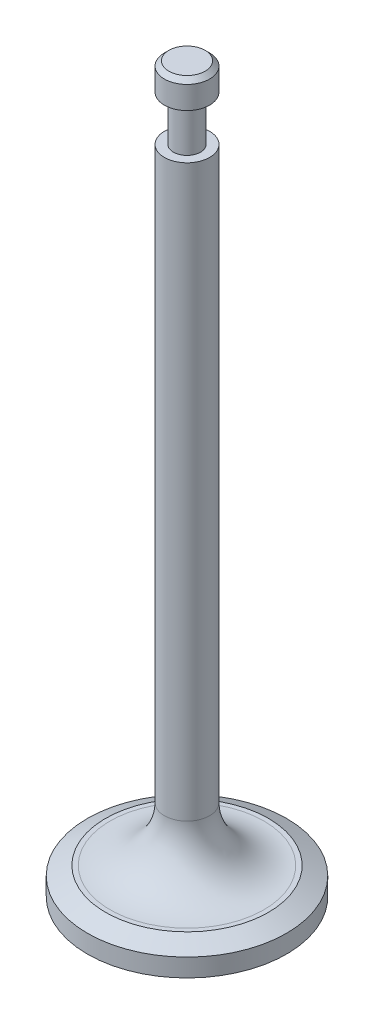
SolidWorks part; units mm, degrees
ref_plane "Front Plane" through (0, 0, 0) normal (0, 0, 1) x (1, 0, 0)
ref_plane "Top Plane" through (0, 0, 0) normal (0, 1, 0) x (1, 0, 0)
ref_plane "Right Plane" through (0, 0, 0) normal (1, 0, 0) x (0, 0, -1)
sketch "Sketch1" plane through (0, 0, 0) normal (1, 0, 0) x (0, 0, -1)
  line L13 (0, 0) -> (0, -80)
  line L14 (0, -80) -> (11, -80)
  line L15 (11, -80) -> (11, -77)
  line L16 (11, -77) -> (2.5, -77)
  line L17 (2.5, -77) -> (2.5, -8)
  line L18 (2.5, -8) -> (1.5, -8)
  line L19 (1.5, -8) -> (1.5, -3)
  line L20 (1.5, -3) -> (2.5, -3)
  line L21 (2.5, -3) -> (2.5, 0)
  line L22 (2.5, 0) -> (0, 0)
  dimension "D1" = 80
  dimension "D2" = 11
  dimension "D3" = 2.5
  dimension "D4" = 2.5
  dimension "D5" = 3
  dimension "D6" = 5
  dimension "D7" = 3
  dimension "D8" = 1
revolve "Revolve1" add sketch "Sketch1" angle 360 about L13
fillet "Fillet1" radius 6 1 edges at (0, -77, 2.5)
chamfer "Chamfer1" distance 1 distance2 2 1 edges at (0, -77, 11)
chamfer "Chamfer2" distance 0.5 angle 45 1 edges at (0, 0, 2.5)
